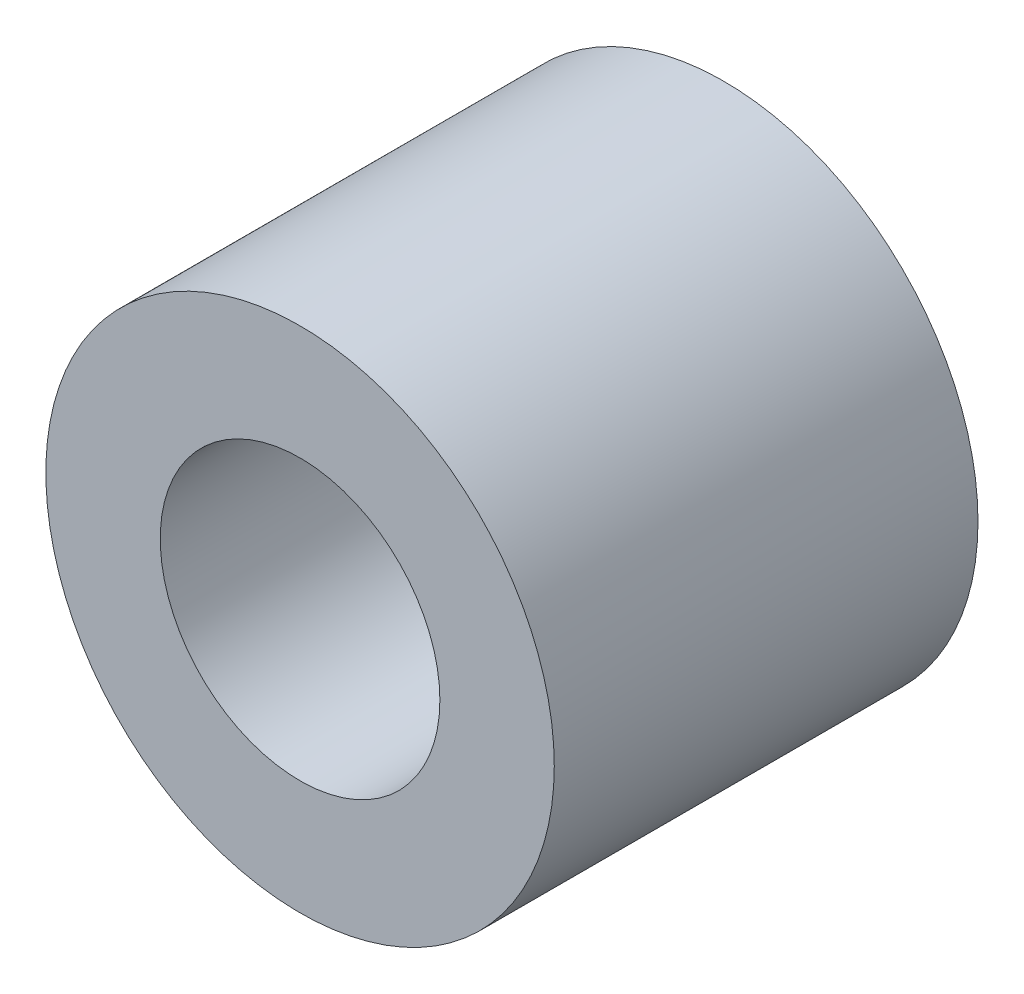
SolidWorks part; units mm, degrees
material "Nylon 101"
ref_plane "Front Plane" through (0, 0, 0) normal (0, 0, 1) x (1, 0, 0)
ref_plane "Top Plane" through (0, 0, 0) normal (0, 1, 0) x (1, 0, 0)
ref_plane "Right Plane" through (0, 0, 0) normal (1, 0, 0) x (0, 0, -1)
sketch "Sketch1" plane through (0, 0, 0) normal (0, 0, 1) x (1, 0, 0)
  circle A0 centre (0, 0) radius 9.525
  circle A1 centre (0, 0) radius 5.2387
  dimension "D1" = 19.05
  dimension "D2" = 10.4775
extrude "Boss-Extrude1" add sketch "Sketch1" along normal mid plane 15.875
equation "\"D1@Boss-Extrude1\"=0.0625in+0.45mm/2"
